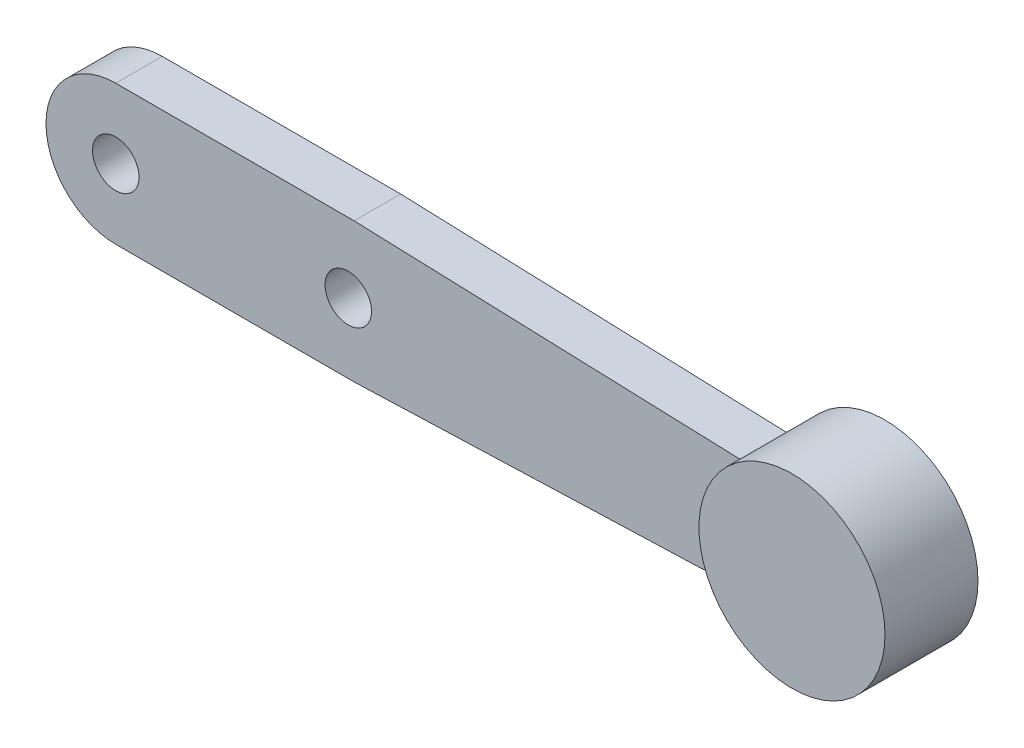
SolidWorks part; units mm, degrees
ref_plane "Front Plane" through (0, 0, 0) normal (0, 0, 1) x (1, 0, 0)
ref_plane "Top Plane" through (0, 0, 0) normal (0, 1, 0) x (1, 0, 0)
ref_plane "Right Plane" through (0, 0, 0) normal (1, 0, 0) x (0, 0, -1)
sketch "Sketch1" plane through (0, 0, 0) normal (0, 0, 1) x (1, 0, 0)
  line L0 (0.6318, 7.5059) -> (50.2015, 5.7749)
  line L1 (0.6318, -7.4941) -> (50.2015, -5.7631)
  line L2 (-1025, 0.0059) -> (48975, 0.0059) construction
  line L3 (0.6318, 7.5059) -> (-25, 7.5059)
  line L4 (0.2967, 2.4823) -> (0.2967, -2.4823)
  line L5 (0.6318, -7.4941) -> (-25, -7.4941)
  line L6 (-25, 7.5059) -> (-25, -7.4941)
  circle A0 centre (0, 0) radius 2.5
  arc A3 (50.2015, -5.7631) -> (50.2015, 5.7749) centre (50, 0.0059) ccw
  circle A4 centre (-25, 0.0059) radius 7.5
  circle A5 centre (-25, 0.0059) radius 2.5
  circle A6 centre (-44.778, 34.7741) radius 2.5 construction
  dimension "D2" = 15
  dimension "D4" = 25
  dimension "D3" = 50
  dimension "D5" = 182
extrude "Boss-Extrude1" add sketch "Sketch1" along normal mid plane 5 contours A4 L2 A5 L6 | A5 L2 A4 L6 | L2 A4 L6 A5 | L2 A5 L6 A4 | L2 A4 L5 L1 A3 A0 | A4 L2 A0 A3 L0 L3
sketch "Sketch2" plane through (0, 0, 0) normal (0, 0, 1) x (1, 0, 0)
  circle A2 centre (50.2015, 0.0059) radius 10
  dimension "D1" = 20
extrude "Boss-Extrude2" add sketch "Sketch2" along normal mid plane 10
